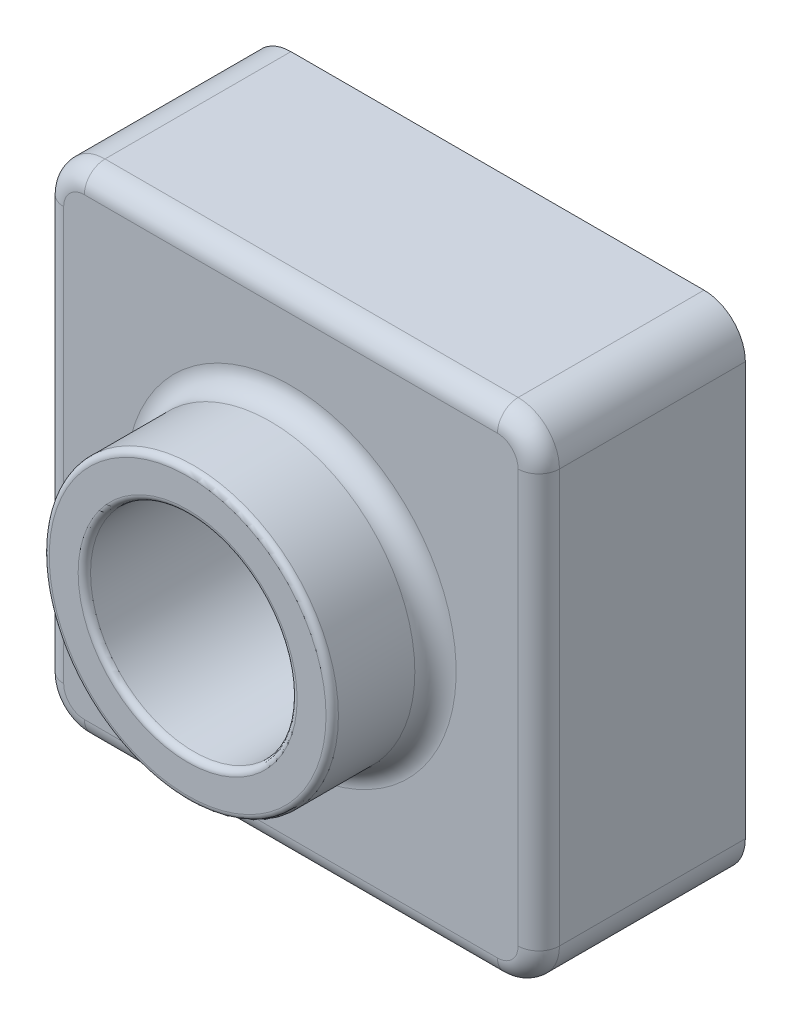
SolidWorks part; units mm, degrees
ref_plane "Front Plane" through (0, 0, 0) normal (0, 0, 1) x (1, 0, 0)
ref_plane "Top Plane" through (0, 0, 0) normal (0, 1, 0) x (1, 0, 0)
ref_plane "Right Plane" through (0, 0, 0) normal (1, 0, 0) x (0, 0, -1)
sketch "Sketch1" plane through (0, 0, 0) normal (0, 0, 1) x (1, 0, 0)
  line L1 (0, 0) -> (120, 0)
  line L2 (0, 0) -> (0, 120)
  line L3 (0, 120) -> (120, 120)
  line L4 (120, 0) -> (120, 120)
  dimension "D1" = 120
  dimension "D2" = 120
extrude "Boss-Extrude1" add sketch "Sketch1" along normal blind 50
sketch "Sketch2" plane through (0, 0, 50) normal (0, 0, 1) x (1, 0, 0)
  line L0 (120, 120) -> (0, 120) construction
  line L1 (120, 0) -> (120, 120) construction
  circle A0 centre (60, 60) radius 35
  dimension "D1" = 70
  dimension "D2" = 60
  dimension "D3" = 60
extrude "Boss-Extrude2" add sketch "Sketch2" along normal blind 25
sketch "Sketch3" plane through (0, 0, 75) normal (0, 0, 1) x (1, 0, 0)
  circle A0 centre (60, 60) radius 25
  dimension "D1" = 50
extrude "Cut-Extrude1" cut sketch "Sketch3" against normal through all
fillet "Fillet1" radius 10 4 edges at (0, 120, 25) (0, 0, 25) (120, 0, 25) (120, 120, 25)
fillet "Fillet2" radius 1.5 2 edges at (95, 60, 75) (85, 60, 75)
fillet "Fillet3" radius 5 9 edges at (117.0711, 117.0711, 50) (120, 60, 50) (117.0711, 2.9289, 50) (60, 0, 50) (2.9289, 2.9289, 50) (0, 60, 50) (2.9289, 117.0711, 50) (60, 120, 50) (95, 60, 50)
shell "Shell1" thickness 2
